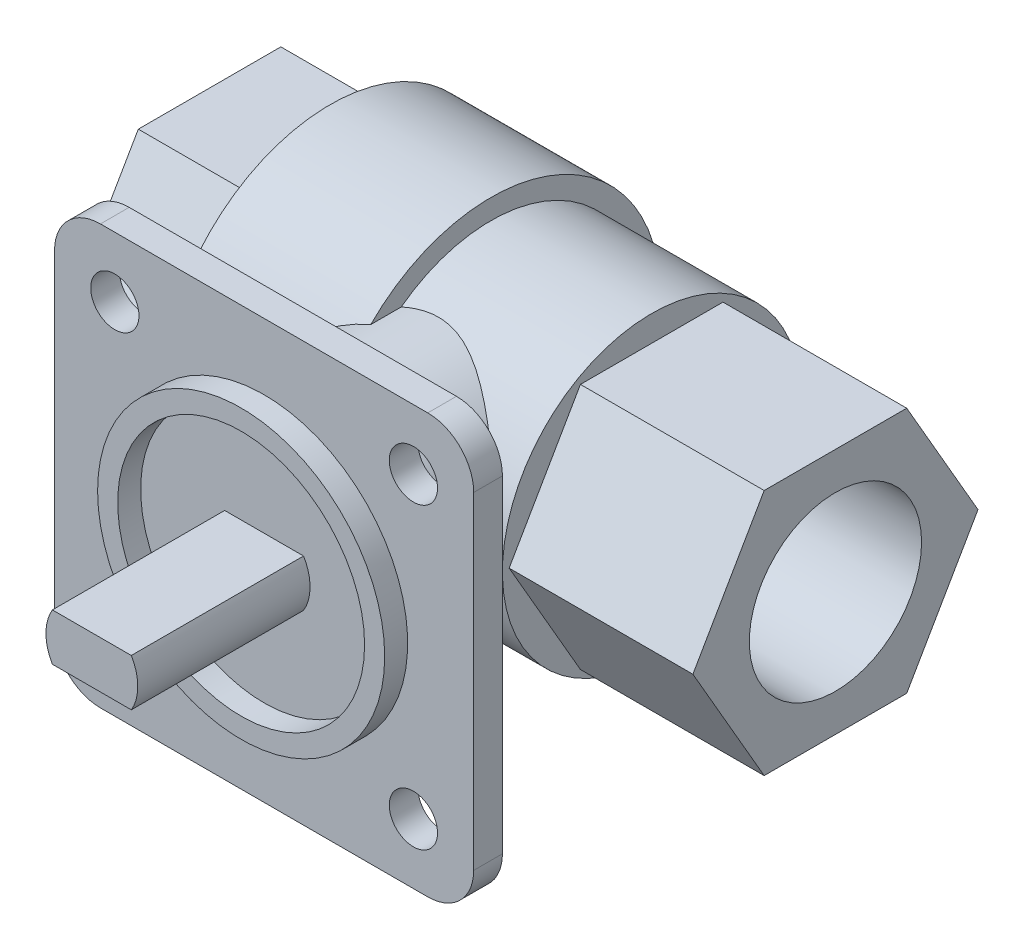
SolidWorks part; units mm, degrees
ref_plane "Front Plane" through (0, 0, 0) normal (1, 0, 0) x (0, 1, 0)
ref_plane "Top Plane" through (0, 0, 0) normal (0, 0, 1) x (0, 1, 0)
ref_plane "Right Plane" through (0, 0, 0) normal (0, 1, 0) x (-1, 0, 0)
sketch "Sketch1" plane through (0, 0, 0) normal (1, 0, 0) x (0, 1, 0)
  line L1 (0, 12.413) -> (-10.75, 6.2065)
  line L2 (-10.75, 6.2065) -> (-10.75, -6.2065)
  line L3 (-10.75, -6.2065) -> (0, -12.413)
  line L4 (0, -12.413) -> (10.75, -6.2065)
  line L5 (10.75, -6.2065) -> (10.75, 6.2065)
  line L6 (10.75, 6.2065) -> (0, 12.413)
  circle A0 centre (0, 0) radius 10.75 construction
  dimension "D1" = 21.5
extrude "Boss-Extrude1" add sketch "Sketch1" along normal blind 10.5
sketch "Sketch2" plane through (10.5, 0, 0) normal (1, 0, 0) x (0, 1, 0)
  circle A0 centre (0, 0) radius 14.75
  dimension "D1" = 29.5
extrude "Boss-Extrude2" add sketch "Sketch2" along normal blind 14
sketch "Sketch3" plane through (24.5, 0, 0) normal (1, 0, 0) x (0, 1, 0)
  circle A0 centre (0, 0) radius 13
  dimension "D1" = 26
extrude "Boss-Extrude3" add sketch "Sketch3" along normal blind 14
sketch "Sketch4" plane through (38.5, 0, 0) normal (1, 0, 0) x (0, 1, 0)
  line L1 (0, 12.413) -> (-10.75, 6.2065)
  line L2 (-10.75, 6.2065) -> (-10.75, -6.2065)
  line L3 (-10.75, -6.2065) -> (0, -12.413)
  line L4 (0, -12.413) -> (10.75, -6.2065)
  line L5 (10.75, -6.2065) -> (10.75, 6.2065)
  line L6 (10.75, 6.2065) -> (0, 12.413)
  circle A0 centre (0, 0) radius 10.75 construction
  dimension "D1" = 21.5
extrude "Boss-Extrude4" add sketch "Sketch4" along normal blind 16
sketch "Sketch5" plane through (0, 0, 0) normal (0, 0, 1) x (0, 1, 0)
  line L0 (-13, -38.5) -> (13, -38.5) construction
  circle A0 centre (0, -27.25) radius 10.75
  dimension "D1" = 21.5
  dimension "D2" = 11.25
extrude "Boss-Extrude5" add sketch "Sketch5" along normal blind 20
sketch "Sketch6" plane through (0, 0, 20) normal (0, 0, 1) x (1, 0, 0)
  line L0 (27.25, 0) -> (27.25, 21.6519) construction
  line L1 (13, -18.25) -> (41.5, -18.25)
  line L2 (9, -14.25) -> (9, 14.25)
  line L3 (13, 18.25) -> (41.5, 18.25)
  line L4 (45.5, -14.25) -> (45.5, 14.25)
  line L5 (9, -18.25) -> (45.5, 18.25) construction
  line L6 (9, 18.25) -> (45.5, -18.25) construction
  line L7 (27.25, 0) -> (12.3177, 0) construction
  arc A0 (13, -18.25) -> (9, -14.25) centre (13, -14.25) cw
  arc A1 (41.5, -18.25) -> (45.5, -14.25) centre (41.5, -14.25) ccw
  arc A2 (41.5, 18.25) -> (45.5, 14.25) centre (41.5, 14.25) cw
  arc A3 (9, 14.25) -> (13, 18.25) centre (13, 14.25) cw
  circle A4 centre (14.25, 13) radius 2.1
  circle A5 centre (40.25, 13) radius 2.1
  circle A6 centre (40.25, -13) radius 2.1
  circle A7 centre (14.25, -13) radius 2.1
  point P0 (27.25, 0)
  dimension "D3" = 4
  dimension "D4" = 4.2
  dimension "D1" = 36.5
  dimension "D2" = 36.5
  dimension "D5" = 13
  dimension "D6" = 13
  dimension "D7" = 2
  dimension "D8" = 2
extrude "Boss-Extrude6" add sketch "Sketch6" along normal blind 2.5
sketch "Sketch7" plane through (54.5, 0, 0) normal (1, 0, 0) x (0, 1, 0)
  circle A0 centre (0, 0) radius 7.5
  dimension "D1" = 15
extrude "Cut-Extrude1" cut sketch "Sketch7" against normal up to next
sketch "Sketch8" plane through (0, 0, 22.5) normal (0, 0, 1) x (1, 0, 0)
  circle A0 centre (27.25, 0) radius 10.75 construction
  circle A1 centre (27.25, 0) radius 10.75
  circle A2 centre (27.25, 0) radius 12.5
  dimension "D1" = 25
extrude "Boss-Extrude7" add sketch "Sketch8" along normal blind 2
sketch "Sketch9" plane through (0, 0, 22.5) normal (0, 0, 1) x (1, 0, 0)
  line L1 (23.8153, -2.05) -> (30.6847, -2.05)
  line L3 (23.8153, 2.05) -> (30.6847, 2.05)
  line L5 (23.6903, -1.8244) -> (30.8097, 1.8244) construction
  line L6 (23.6903, 1.8244) -> (30.8097, -1.8244) construction
  arc A2 (23.8153, 2.05) -> (23.8153, -2.05) centre (27.25, 0) ccw
  arc A3 (30.6847, -2.05) -> (30.6847, 2.05) centre (27.25, 0) ccw
extrude "Boss-Extrude8" add sketch "Sketch9" along normal blind 15
